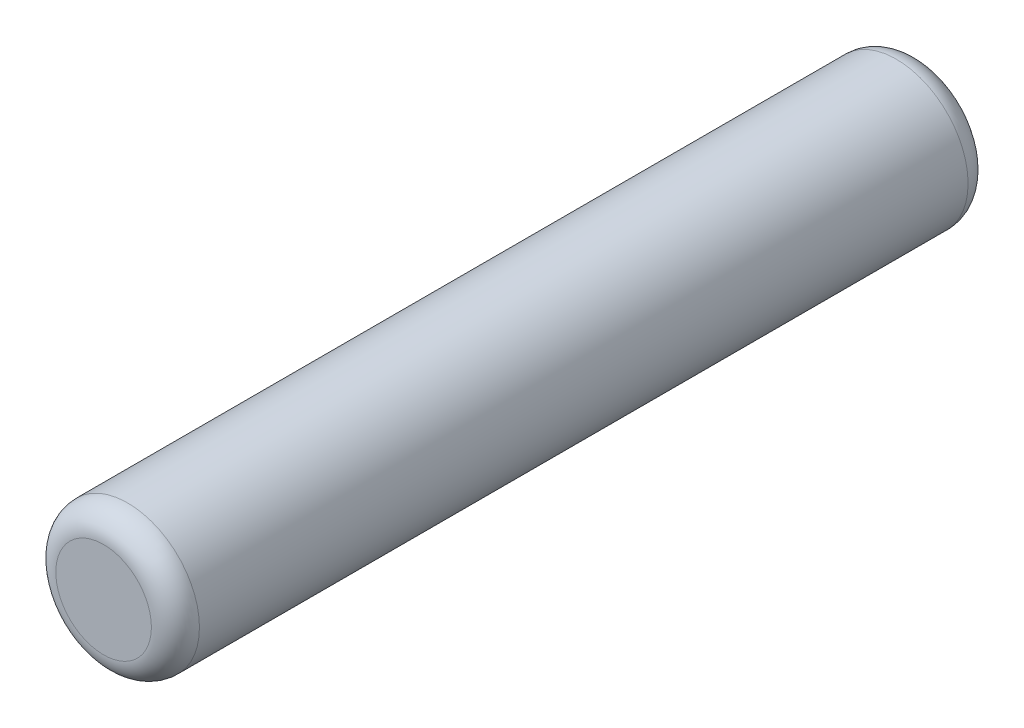
SolidWorks part; units mm, degrees
ref_plane "Front Plane" through (0, 0, 0) normal (0, 0, 1) x (1, 0, 0)
ref_plane "Top Plane" through (0, 0, 0) normal (0, 1, 0) x (1, 0, 0)
ref_plane "Right Plane" through (0, 0, 0) normal (1, 0, 0) x (0, 0, -1)
sketch "Sketch2" plane through (0, 0, 0) normal (0, 0, 1) x (1, 0, 0)
  circle A0 centre (0, 0) radius 1.495
  dimension "D1" = 2.99
extrude "Boss-Extrude3" add sketch "Sketch2" against normal blind 17
fillet "Fillet2" radius 0.5 2 edges at (1.495, 0, -17) (1.495, 0, 0)
